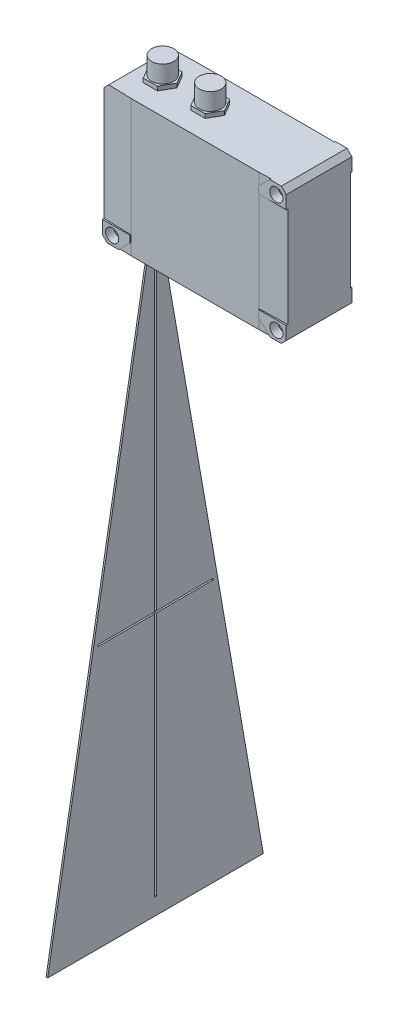
SolidWorks part; units mm, degrees
ref_plane "Přední rovina" through (0, 0, 0) normal (0, 0, 1) x (1, 0, 0)
ref_plane "Horní rovina" through (0, 0, 0) normal (0, 1, 0) x (1, 0, 0)
ref_plane "Pravá rovina" through (0, 0, 0) normal (1, 0, 0) x (0, 0, -1)
sketch "Skica1" plane through (0, 0, 0) normal (0, 0, 1) x (1, 0, 0)
  line L0 (0, 0) -> (0, 83) construction
  line L2 (-56, 83) -> (56, 83)
  line L3 (-56, 83) -> (-56, 0)
  line L4 (-56, 0) -> (56, 0)
  line L5 (56, 83) -> (56, 0)
  dimension "D1" = 112
  dimension "D2" = 83
extrude "Přidat vysunutím1" add sketch "Skica1" against normal blind 39
sketch "Skica2" plane through (0, 0, 0) normal (0, 0, 1) x (1, 0, 0)
  line L0 (-50, 83) -> (-50, 0) construction
  line L1 (56, 83) -> (-56, 83) construction
  line L2 (-56, 0) -> (56, 0) construction
  line L3 (50, 83) -> (50, 0) construction
  line L4 (-56, 5.5) -> (56, 5.5) construction
  line L5 (-56, 83) -> (-56, 0) construction
  line L6 (56, 0) -> (56, 83) construction
  line L7 (-56, 77) -> (56, 77) construction
  circle A0 centre (50, 77) radius 2
  circle A1 centre (-50, 5.5) radius 2
  circle A2 centre (50, 5.5) radius 2
  dimension "D5" = 4
  dimension "D1" = 77
  dimension "D2" = 6
  dimension "D3" = 6
  dimension "D4" = 5.5
extrude "Odebrat vysunutím1" cut sketch "Skica2" against normal through all
sketch "Skica3" plane through (0, 0, 0) normal (0, 0, 1) x (1, 0, 0)
  circle A0 centre (50, 77) radius 4
  circle A1 centre (50, 5.5) radius 4
  circle A2 centre (-50, 5.5) radius 4
  dimension "D1" = 8
extrude "Odebrat vysunutím2" cut sketch "Skica3" against normal blind 4.5
sketch "Skica4" plane through (0, 0, -39) normal (0, 0, -1) x (-1, 0, 0)
  circle A0 centre (-50, 77) radius 4
  circle A1 centre (-50, 5.5) radius 4
  circle A2 centre (50, 5.5) radius 4
  dimension "D1" = 8
extrude "Odebrat vysunutím3" cut sketch "Skica4" against normal blind 4.5
chamfer "Zkosení1" distance 3 angle 45 4 edges at (-56, 0, -19.5) (56, 0, -19.5) (56, 83, -19.5) (-56, 83, -19.5)
sketch "Skica5" plane through (0, 83, 0) normal (0, 1, 0) x (1, 0, 0)
  line L0 (-56, 19.5) -> (56, 19.5) construction
  line L1 (-56, 0) -> (-56, 39) construction
  line L2 (56, 39) -> (56, 0) construction
  circle A0 centre (-39.25, 19.5) radius 6.75
  circle A1 centre (-10.25, 19.5) radius 6.75
  point P10 (-46, 19.5)
  dimension "D2" = 13.5
  dimension "D1" = 29
  dimension "D3" = 10
extrude "Přidat vysunutím2" add sketch "Skica5" along normal blind 13
sketch "Skica6" plane through (0, 83, 0) normal (0, 1, 0) x (1, 0, 0)
  line L1 (-34.9199, 27) -> (-43.5801, 27)
  line L2 (-43.5801, 27) -> (-47.9103, 19.5)
  line L3 (-47.9103, 19.5) -> (-43.5801, 12)
  line L4 (-43.5801, 12) -> (-34.9199, 12)
  line L5 (-34.9199, 12) -> (-30.5897, 19.5)
  line L6 (-30.5897, 19.5) -> (-34.9199, 27)
  line L7 (-5.9199, 27) -> (-14.5801, 27)
  line L8 (-14.5801, 27) -> (-18.9103, 19.5)
  line L9 (-18.9103, 19.5) -> (-14.5801, 12)
  line L10 (-14.5801, 12) -> (-5.9199, 12)
  line L11 (-5.9199, 12) -> (-1.5897, 19.5)
  line L12 (-1.5897, 19.5) -> (-5.9199, 27)
  circle A0 centre (-39.25, 19.5) radius 7.5 construction
  circle A1 centre (-10.25, 19.5) radius 7.5 construction
  dimension "D1" = 15
extrude "Přidat vysunutím3" add sketch "Skica6" along normal blind 2.5
sketch "Skica7" plane through (0, 0, 0) normal (0, -1, 0) x (1, 0, 0)
  line L0 (-56, -19.5) -> (56, -19.5) construction
  line L1 (-56, -39) -> (-56, 0) construction
  line L2 (56, 0) -> (56, -39) construction
  line L4 (22.7, -9.5) -> (40, -9.5)
  line L5 (22.7, -9.5) -> (22.7, -29.5)
  line L6 (22.7, -29.5) -> (40, -29.5)
  line L7 (40, -9.5) -> (40, -29.5)
  line L8 (-48, -9.5) -> (-40, -9.5)
  line L9 (-48, -9.5) -> (-48, -29.5)
  line L10 (-48, -29.5) -> (-40, -29.5)
  line L11 (-40, -9.5) -> (-40, -29.5)
  dimension "D1" = 16
  dimension "D2" = 17.3
  dimension "D3" = 20
  dimension "D4" = 20
  dimension "D5" = 8
  dimension "D6" = 8
extrude "Odebrat vysunutím4" cut sketch "Skica7" against normal blind 0.5
sketch "Skica8" plane through (0, 83, 0) normal (0, 1, 0) x (1, 0, 0)
  line L0 (-39, 39) -> (-56, 38.5)
  line L1 (53, 39) -> (-53, 39) construction
  line L2 (-56, 0) -> (-56, 39) construction
  line L3 (-56, 38.5) -> (-56, 39)
  line L4 (-56, 39) -> (-39, 39)
  line L5 (-56, 19.5) -> (56, 19.5) construction
  line L6 (56, 39) -> (56, 0) construction
  line L7 (-56, 0) -> (-39, 0)
  line L8 (-56, 0.5) -> (-56, 0)
  line L9 (-39, 0) -> (-56, 0.5)
  line L10 (0, 39) -> (0, 0) construction
  line L11 (53, 0) -> (-53, 0) construction
  line L12 (39, 0) -> (56, 0.5)
  line L13 (56, 0.5) -> (56, 0)
  line L14 (56, 0) -> (39, 0)
  line L15 (56, 39) -> (39, 39)
  line L16 (56, 38.5) -> (56, 39)
  line L17 (39, 39) -> (56, 38.5)
  dimension "D1" = 17
  dimension "D2" = 0.5
extrude "Odebrat vysunutím5" cut sketch "Skica8" against normal through all
sketch "Skica10" plane through (0, 0, 0) normal (0, 0, 1) x (1, 0, 0)
  line L1 (53, 83) -> (39, 83) construction
  line L2 (56, 80) -> (53, 83) construction
  line L3 (39, 0) -> (39, 83) construction
  line L12 (56, 3) -> (56, 80) construction
  line L13 (53, 0) -> (56, 3) construction
  line L14 (53, 0) -> (39, 0) construction
  line L15 (-39, 0) -> (-39, 83) construction
  line L16 (-39, 0) -> (-53, 0) construction
  line L17 (-56, 3) -> (-53, 0) construction
  line L18 (-56, 3) -> (-56, 80) construction
  line L19 (53, 83) -> (46, 83)
  line L20 (56, 80) -> (53, 83)
  line L21 (39, 7) -> (39, 11)
  line L22 (56, 3) -> (56, 80)
  line L23 (53, 0) -> (56, 3)
  line L24 (53, 0) -> (46, 0)
  line L25 (-39, 7) -> (-39, 11)
  line L26 (-46, 0) -> (-53, 0)
  line L27 (-56, 3) -> (-53, 0)
  line L28 (-56, 3) -> (-56, 80)
  line L29 (-56, 11) -> (-39, 11)
  line L30 (56, 72) -> (39, 72)
  line L31 (39, 11) -> (56, 11)
  line L32 (39, 72) -> (39, 76)
  line L33 (-46, 0) -> (-39, 7)
  line L34 (46, 0) -> (39, 7)
  line L35 (46, 83) -> (39, 76)
  circle A0 centre (50, 77) radius 4 construction
  circle A1 centre (50, 5.5) radius 4 construction
  circle A2 centre (-50, 5.5) radius 4 construction
  circle A3 centre (50, 77) radius 4
  circle A4 centre (50, 5.5) radius 4
  circle A5 centre (-50, 5.5) radius 4
  line M5 (39, 0) -> (39, 83)
  line M7 (-39, 83) -> (-39, 0)
  dimension "D1" = 11
  dimension "D2" = 11
  dimension "D3" = 10
  dimension "D4" = 45
  dimension "D5" = 10
  dimension "D6" = 10
extrude "Přidat vysunutím4" add sketch "Skica10" along normal blind 0.5 and the other way up to body contours L26 L33 L29 L28 L27 A5 M7 | L34 L24 L23 L22 L31 A4 M5 | L19 L35 L30 L22 L20 A3 M5
ref_plane "Rovina1" through (0, 0, -19.5) normal (0, 0, 1) x (1, 0, 0)
mirror "Zrcadlit1" about plane through (0, 0, -19.5) normal (0, 0, 1) of "Přidat vysunutím4"
ref_plane "Rovina2" through (-44, 0, 0) normal (-1, 0, 0) x (0, 0, 1)
sketch "Skica11" plane through (-44, 0, -44) normal (1, 0, 0) x (0, 0, -1)
  line L2 (-34.5, 0) -> (-14.5, 0) construction
  line L6 (-27.5875, 0) -> (-21.6125, 0)
  line L7 (-24.6, -0.1) -> (-24.6, -360) construction
  line L8 (-27.5875, 0) -> (-90.25, -360)
  line L9 (-90.25, -360) -> (41.05, -360)
  line L10 (-21.6125, 0) -> (41.05, -360)
  point P6 (-62.4, -200)
  point P10 (13.2, -200)
  dimension "D1" = 200
  dimension "D2" = 360
  dimension "D3" = 75.6
  dimension "D4" = 131.3
extrude "Přidat vysunutím5" add sketch "Skica11" along normal mid plane 1 separate body
sketch "Skica12" plane through (-44.5, 0, 0) normal (-1, 0, 0) x (0, 0, 1)
  line L0 (-57.2, -200) -> (18.4, -200) construction
  line L1 (-85.05, -360) -> (-22.3875, 0) construction
  line L2 (-16.4125, 0) -> (46.25, -360) construction
  line L3 (-22.3875, 0) -> (-16.4125, 0) construction
  line L4 (-19.4, 0) -> (-19.4, -360) construction
  line L5 (-54.4, -200.5) -> (-19.9, -200.5)
  line L6 (-54.4, -200.5) -> (-54.4, -199.5)
  line L7 (-54.4, -199.5) -> (-19.9, -199.5)
  line L8 (15.6, -200.5) -> (15.6, -199.5)
  line L9 (-54.4, -200.5) -> (15.6, -199.5) construction
  line L10 (-54.4, -199.5) -> (15.6, -200.5) construction
  line L11 (46.25, -360) -> (-85.05, -360) construction
  line L13 (-19.9, -350) -> (-18.9, -350)
  line L14 (-19.9, -350) -> (-19.9, -200.5)
  line L15 (-19.9, -10) -> (-18.9, -10)
  line L16 (-18.9, -350) -> (-18.9, -200.5)
  line L17 (-19.9, -350) -> (-18.9, -10) construction
  line L18 (-19.9, -10) -> (-18.9, -350) construction
  line L19 (-18.9, -199.5) -> (15.6, -199.5)
  line L20 (-18.9, -199.5) -> (-18.9, -10)
  line L22 (-18.9, -200.5) -> (15.6, -200.5)
  line L24 (-19.9, -199.5) -> (-19.9, -10)
  point P8 (-19.4, -200)
  point P17 (-19.4, -180)
  dimension "D1" = 200
  dimension "D2" = 1
  dimension "D3" = 70
  dimension "D4" = 1
  dimension "D5" = 340
extrude "Odebrat vysunutím6" cut sketch "Skica12" against normal through all both and the other way through all
ref_plane "Rovina3" through (-44, 0, 0) normal (-1, 0, 0) x (0, 0, 1)
